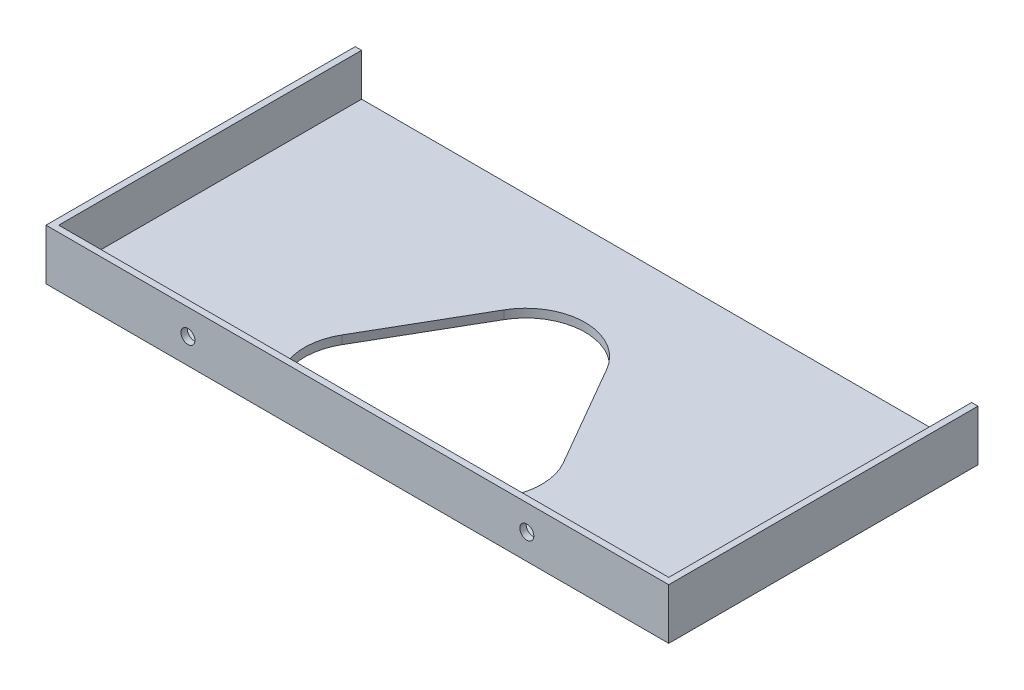
SolidWorks part; units mm, degrees
ref_plane "前视基准面" through (0, 0, 0) normal (0, 0, 1) x (1, 0, 0)
ref_plane "上视基准面" through (0, 0, 0) normal (0, 1, 0) x (1, 0, 0)
ref_plane "右视基准面" through (0, 0, 0) normal (1, 0, 0) x (0, 0, -1)
sketch "草图1" plane through (0, 0, 0) normal (0, 1, 0) x (1, 0, 0)
  line L1 (0, 0) -> (147, 0)
  line L2 (0, 0) -> (0, 76)
  line L3 (0, 76) -> (147, 76)
  line L4 (147, 0) -> (147, 76)
  dimension "D1" = 147
  dimension "D2" = 76
extrude "凸台-拉伸1" add sketch "草图1" along normal blind 12
sketch "草图2" plane through (0, 12, 0) normal (0, 1, 0) x (1, 0, 0)
  line L8 (1.5, 74.5) -> (1.5, 1.5)
  line L9 (1.5, 1.5) -> (145.5, 1.5)
  line L10 (145.5, 1.5) -> (145.5, 74.5)
  line L11 (145.5, 74.5) -> (1.5, 74.5)
  line L12 (1.5, 74.5) -> (1.5, 1.5)
  line L13 (1.5, 1.5) -> (145.5, 1.5)
  line L14 (145.5, 1.5) -> (145.5, 74.5)
  line L15 (145.5, 74.5) -> (1.5, 74.5)
  dimension "D1" = 1.5
extrude "切除-拉伸1" cut sketch "草图2" against normal offset from surface (10 mm away) 2 up to face at (73.5, 0, -38)
sketch "草图3" plane through (0, 0, -76) normal (0, 0, -1) x (-1, 0, 0)
  line L0 (-147, 6) -> (0, 6) construction
  line L1 (-147, 12) -> (-147, 0) construction
  line L2 (0, 12) -> (0, 0) construction
  line L3 (-73.5, 6) -> (-73.5, 17.272) construction
  circle A0 centre (-113.5, 6) radius 1.65
  circle A1 centre (-33.5, 6) radius 1.65
  dimension "D1" = 3.3
  dimension "D2" = 80
extrude "切除-拉伸2" cut sketch "草图3" against normal through all
sketch "草图5" plane through (0, 0, 0) normal (0, -1, 0) x (1, 0, 0)
  line L0 (73.5, 0) -> (73.5, -1.5) construction
  line L1 (0, 0) -> (147, 0) construction
  line L2 (61.3756, -46.7487) -> (47.3756, -22.5)
  line L3 (59.5, -1.5) -> (87.5, -1.5)
  line L4 (99.6244, -22.5) -> (85.6244, -46.7487)
  line L5 (73.5, -25.7487) -> (73.5, -54.4292) construction
  arc A0 (61.3756, -46.7487) -> (85.6244, -46.7487) centre (73.5, -39.7487) ccw
  arc A1 (59.5, -1.5) -> (47.3756, -22.5) centre (59.5, -15.5) ccw
  arc A2 (99.6244, -22.5) -> (87.5, -1.5) centre (87.5, -15.5) ccw
  dimension "D1" = 28
  dimension "D2" = 14
  dimension "D3" = 1.5
  dimension "D5" = 28
  dimension "D4" = 28
  dimension "D6" = 28
extrude "切除-拉伸3" cut sketch "草图5" against normal blind 10
sketch "草图6" plane through (0, 12, 0) normal (0, 1, 0) x (1, 0, 0)
  line L0 (147, 0) -> (147, 76) construction
  line L1 (0, 76) -> (147, 76)
  line L2 (0, 76) -> (0, 73)
  line L3 (0, 73) -> (147, 73)
  line L4 (147, 76) -> (147, 73)
  dimension "D1" = 3
extrude "切除-拉伸4" cut sketch "草图6" against normal through all
